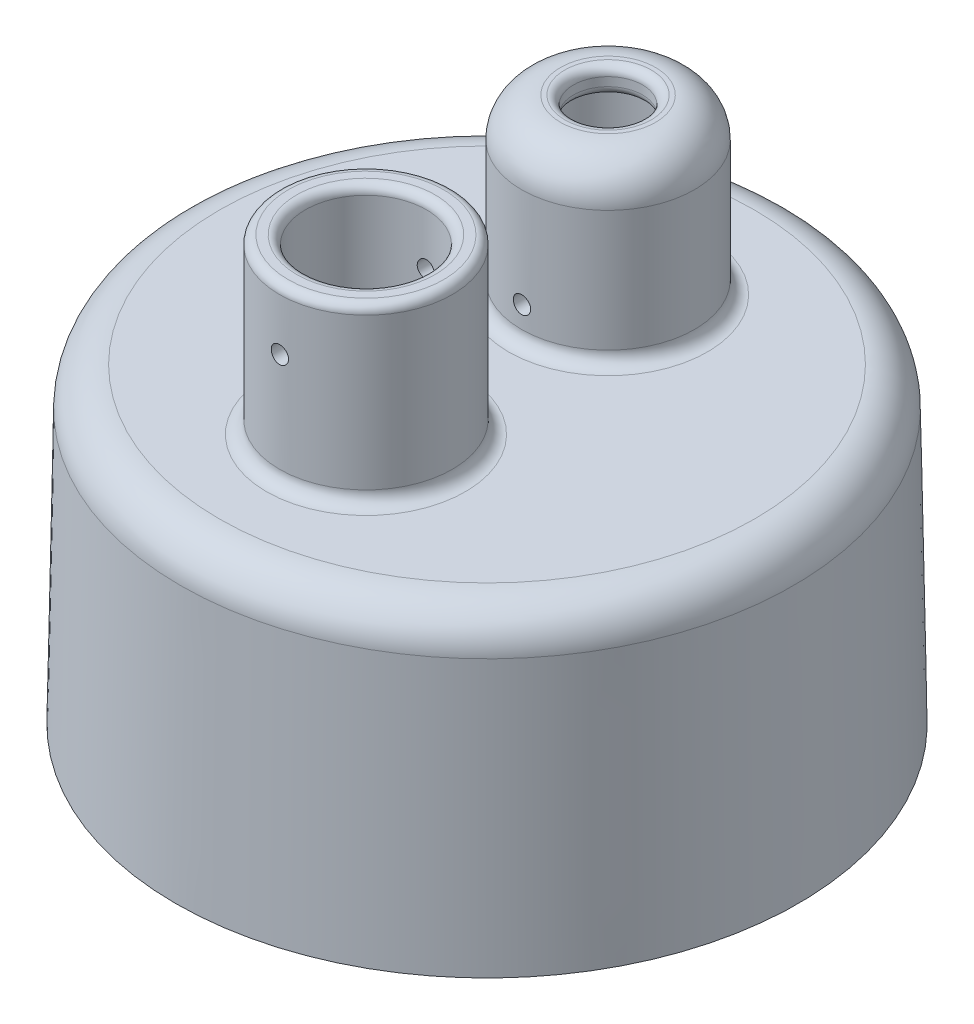
SolidWorks part; units mm, degrees
ref_plane "Front Plane" through (0, 0, 0) normal (0, 0, 1) x (1, 0, 0)
ref_plane "Top Plane" through (0, 0, 0) normal (0, 1, 0) x (1, 0, 0)
ref_plane "Right Plane" through (0, 0, 0) normal (1, 0, 0) x (0, 0, -1)
sketch "Sketch1" plane through (0, 0, 0) normal (0, 1, 0) x (1, 0, 0)
  circle A0 centre (0, 0) radius 18
  dimension "D1" = 36
extrude "Boss-Extrude1" add sketch "Sketch1" along normal blind 18
sketch "Sketch2" plane through (0, 0, 0) normal (0, -1, 0) x (-1, 0, 0)
  circle A0 centre (0, 0) radius 16.5
  dimension "D1" = 33
extrude "Cut-Extrude1" cut sketch "Sketch2" against normal blind 16.5 contours A0
cosmetic thread "Cosmetic Thread1" parameters "D2"=36
sketch "Sketch3" plane through (0, 0, 0) normal (0, 1, 0) x (1, 0, 0)
  line L0 (22.0219, 0) -> (-23.1883, 0) construction
  line L1 (0, -17.7762) -> (0, 19.3158) construction
  circle A0 centre (0, -7) radius 5
  circle A3 centre (0, -7) radius 3.5
  circle A4 centre (0, 7) radius 5
  circle A5 centre (0, 7) radius 2
  dimension "D2" = 10
  dimension "D3" = 7
  dimension "D4" = 4
  dimension "D1" = 7
draft "Draft1" type of draft neutral plane draft angle 1 faces to draft 1 face at (0, 18, 18) neutral plane through (0, 0, 0) neutral plane normal (0, -1, 0) reverse direction yes parameters "D1"=1
extrude "Boss-Extrude2" add sketch "Sketch3" along normal blind 10 from surface at 18 starting at face at (0, 18, 17.6858)
sketch "Sketch4" plane through (0, 18, 0) normal (0, 1, 0) x (1, 0, 0)
  line L0 (0, -10.8243) -> (0, 9.5646) construction
  line L1 (22.2446, 0) -> (-22.4047, 0) construction
  circle A0 centre (0, -7) radius 2
  circle A1 centre (0, 7) radius 3.5
  circle A2 centre (0, -7) radius 3.5 construction
  dimension "D1" = 4
  dimension "D2" = 7
extrude "Cut-Extrude3" cut sketch "Sketch4" along normal blind 8.5 and the other way up to next
fillet "Fillet4" radius 0.5 6 edges at (0, 28, -5) (0, 28, 12) (0, 28, 10.5) (0, 26.5, -9) (0, 16.5, 5) (0, 18, 9)
sketch "Sketch6" plane through (0, 0, 0) normal (0, 0, 1) x (1, 0, 0)
  line L0 (0, 31.4165) -> (0, -7.0133) construction
  circle A0 centre (0, 20) radius 0.5
  dimension "D2" = 1
  dimension "D1" = 20
sketch "Sketch7" plane through (0, 0, 0) normal (0, 0, 1) x (1, 0, 0)
  line L0 (0, 30.4165) -> (0, -8.0133) construction
  circle A1 centre (0, 24.5) radius 0.5
  dimension "D3" = 1
  dimension "D1" = 24.5
extrude "Cut-Extrude4" cut sketch "Sketch6" against normal through all
extrude "Cut-Extrude5" cut sketch "Sketch7" along normal through all
fillet "Fillet5" radius 0.75 5 edges at (0, 26.5, -10.5) (0, 16.5, -16.5) (0, 18, 12) (0, 18, -2) (0, 18, 10.5)
fillet "Fillet6" radius 2.25 3 edges at (0, 28, -2) (0, 18, 17.6858) (0, 16.5, -10.5)
equation "\"50eg\"=1"
